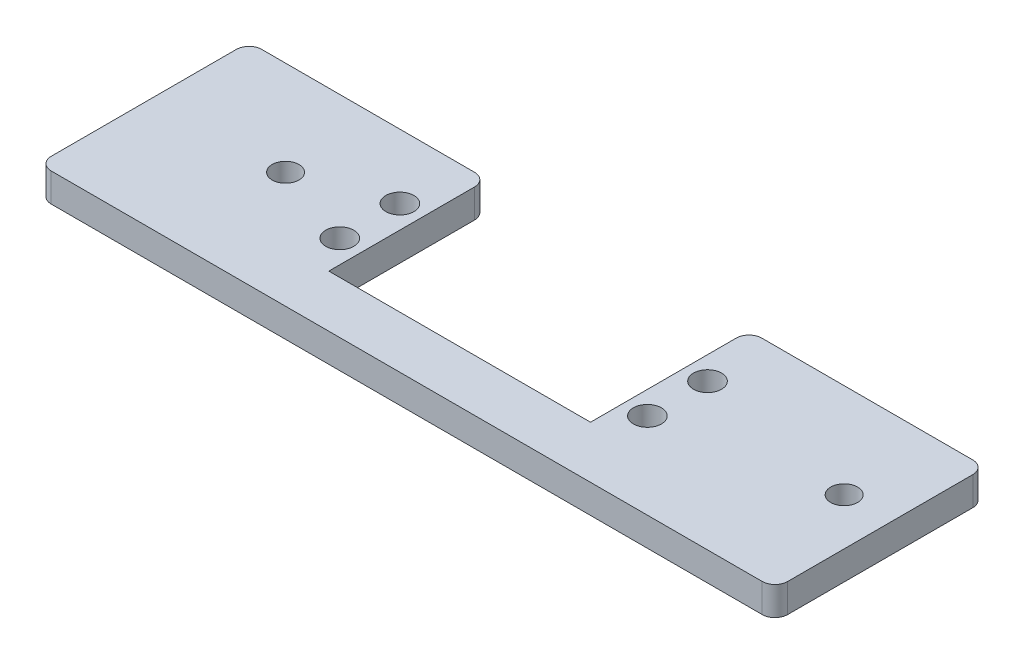
SolidWorks part; units mm, degrees
ref_plane "Front Plane" through (0, 0, 0) normal (0, 0, 1) x (1, 0, 0)
ref_plane "Top Plane" through (0, 0, 0) normal (0, 1, 0) x (1, 0, 0)
ref_plane "Right Plane" through (0, 0, 0) normal (1, 0, 0) x (0, 0, -1)
sketch "Sketch1" plane through (0, 0, 0) normal (0, 1, 0) x (1, 0, 0)
  line L1 (55.75, 16.51) -> (22.6581, 16.51)
  line L2 (57.75, 14.51) -> (57.75, -14.51)
  line L3 (55.75, -16.51) -> (-55.75, -16.51)
  line L4 (-57.75, 14.51) -> (-57.75, -14.51)
  line L5 (57.75, 16.51) -> (-57.75, -16.51) construction
  line L6 (57.75, -16.51) -> (-57.75, 16.51) construction
  line L7 (-57.75, 1.69) -> (57.75, 1.69) construction
  line L8 (-20.3883, 14.51) -> (-20.3883, -8.345)
  line L9 (20.6581, 14.51) -> (20.6581, -8.345)
  line L10 (-20.3883, -8.345) -> (20.6581, -8.345)
  line L11 (0.1349, -8.345) -> (0.1349, 16.51) construction
  line L12 (-22.3883, 16.51) -> (-55.75, 16.51)
  line L13 (10.9045, 16.51) -> (10.9045, -8.345) construction
  circle A0 centre (-37.2031, 1.69) radius 2.1082
  circle A1 centre (50.4015, 1.69) radius 2.1082
  circle A3 centre (-23.9883, 6.405) radius 2.2
  circle A4 centre (24.2581, 6.405) radius 2.2
  circle A5 centre (24.2581, -3.025) radius 2.2
  circle A6 centre (-23.9883, -3.025) radius 2.2
  arc A7 (-20.3883, 14.51) -> (-22.3883, 16.51) centre (-22.3883, 14.51) ccw
  arc A8 (20.6581, 14.51) -> (22.6581, 16.51) centre (22.6581, 14.51) cw
  arc A9 (55.75, 16.51) -> (57.75, 14.51) centre (55.75, 14.51) cw
  arc A10 (57.75, -14.51) -> (55.75, -16.51) centre (55.75, -14.51) cw
  arc A11 (-55.75, -16.51) -> (-57.75, -14.51) centre (-55.75, -14.51) cw
  arc A12 (-55.75, 16.51) -> (-57.75, 14.51) centre (-55.75, 14.51) ccw
  point P0 (0, 0)
  point P32 (-20.3883, 16.51)
  dimension "D2" = 4.2164
  dimension "D12" = 4.4
  dimension "D13" = 2
  dimension "D1" = 14.82
  dimension "D3" = 9.7536
  dimension "D4" = 115.5
  dimension "D5" = 39.497
  dimension "D6" = 48.1076
  dimension "D7" = 41.0464
  dimension "D8" = 31.2928
  dimension "D9" = 4.715
  dimension "D10" = 33.02
  dimension "D11" = 3.6
  dimension "D14" = 87.6046
  dimension "D15" = 57.8849
  dimension "D16" = 57.6151
extrude "Boss-Extrude1" add sketch "Sketch1" along normal blind 4.5
